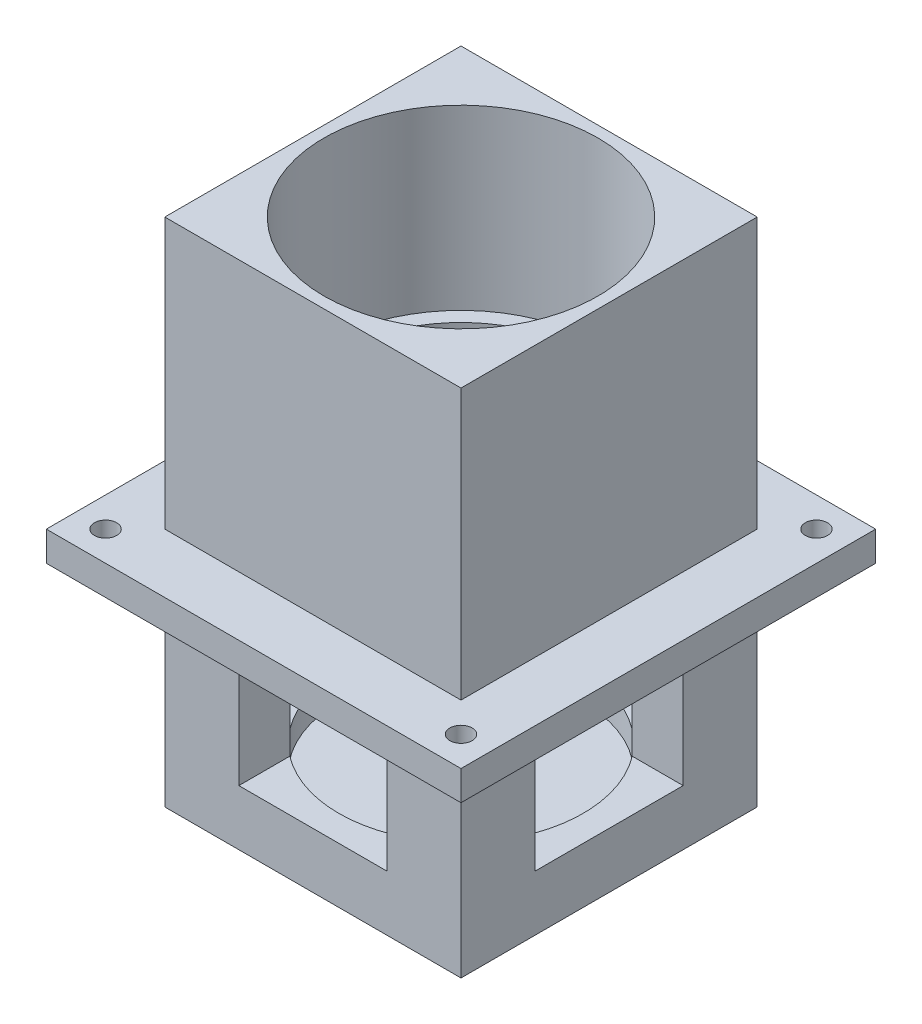
SolidWorks part; units mm, degrees
ref_plane "Front Plane" through (0, 0, 0) normal (0, 0, 1) x (1, 0, 0)
ref_plane "Top Plane" through (0, 0, 0) normal (0, 1, 0) x (1, 0, 0)
ref_plane "Right Plane" through (0, 0, 0) normal (1, 0, 0) x (0, 0, -1)
sketch "Sketch1" plane through (0, 0, 0) normal (0, 1, 0) x (1, 0, 0)
  line L1 (-20, -20) -> (20, -20)
  line L2 (-20, -20) -> (-20, 20)
  line L3 (-20, 20) -> (20, 20)
  line L4 (20, -20) -> (20, 20)
  line L5 (-20, -20) -> (20, 20) construction
  line L6 (-20, 20) -> (20, -20) construction
  point P0 (0, 0)
extrude "Boss-Extrude1" add sketch "Sketch1" along normal blind 90
sketch "Sketch2" plane through (0, 90, 0) normal (0, 1, 0) x (1, 0, 0)
  circle A0 centre (0, 0) radius 18.5
extrude "Cut-Extrude1" cut sketch "Sketch2" against normal blind 45
sketch "Sketch3" plane through (0, 45, 0) normal (0, 1, 0) x (1, 0, 0)
  circle A0 centre (0, 0) radius 16.5
extrude "Cut-Extrude2" cut sketch "Sketch3" against normal blind 41
sketch "Sketch4" plane through (0, 90, 0) normal (0, 1, 0) x (1, 0, 0)
  line L1 (-20, -20) -> (20, -20)
  line L2 (-20, -20) -> (-20, 20)
  line L3 (-20, 20) -> (20, 20)
  line L4 (20, -20) -> (20, 20)
  line L5 (-20, -20) -> (20, 20) construction
  line L6 (-20, 20) -> (20, -20) construction
  point P0 (0, 0)
extrude "Cut-Extrude3" cut sketch "Sketch4" against normal blind 21
sketch "Sketch6" plane through (0, 0, 20) normal (0, 0, 1) x (1, 0, 0)
  line L0 (0, 0) -> (0, 15) construction
  line L2 (-10, 7.5) -> (10, 7.5)
  line L3 (-10, 7.5) -> (-10, 22.5)
  line L4 (-10, 22.5) -> (10, 22.5)
  line L5 (10, 7.5) -> (10, 22.5)
  line L6 (-10, 7.5) -> (10, 22.5) construction
  line L7 (-10, 22.5) -> (10, 7.5) construction
extrude "Cut-Extrude4" cut sketch "Sketch6" against normal through all contours L3 L2 L5 L4
sketch "Sketch8" plane through (-20, 0, 0) normal (-1, 0, 0) x (0, 0, 1)
  line L0 (0, 0) -> (0, 15) construction
  line L2 (-10, 7.5) -> (10, 7.5)
  line L3 (-10, 7.5) -> (-10, 22.5)
  line L4 (-10, 22.5) -> (10, 22.5)
  line L5 (10, 7.5) -> (10, 22.5)
  line L6 (-10, 7.5) -> (10, 22.5) construction
  line L7 (-10, 22.5) -> (10, 7.5) construction
extrude "Cut-Extrude5" cut sketch "Sketch8" against normal through all contours L3 L2 L5 L4
sketch "Sketch11" plane through (0, 0, 20) normal (0, 0, 1) x (1, 0, 0)
  line L0 (0, 0) -> (0, 28.5) construction
  line L1 (-20, 0) -> (20, 0) construction
  line L2 (-20, 28.5) -> (20, 28.5) construction
  line L3 (20, 69) -> (20, 0) construction
  line L4 (-20, 28.5) -> (-20, 15.8) construction
  line L5 (-20, 69) -> (-20, 0) construction
  line L7 (-20, 15.8) -> (20, 15.8) construction
  line L8 (-20, 15.8) -> (-20, 69)
  line L9 (-20, 69) -> (20, 69)
  line L10 (20, 15.8) -> (20, 69)
  line L11 (-20, 28.5) -> (20, 28.5)
  line L12 (-20, 28.5) -> (-20, 0)
  line L13 (-20, 0) -> (20, 0)
  line L14 (20, 28.5) -> (20, 0)
  point P9 (0, 28.5)
sketch "Sketch16" plane through (0, 0, 20) normal (0, 0, 1) x (1, 0, 0)
  line L0 (20, 15.8) -> (20, 69) construction
  line L1 (-20, 28.5) -> (20, 28.5)
  line L2 (-20, 28.5) -> (-20, 32.5)
  line L3 (-20, 32.5) -> (20, 32.5)
  line L4 (20, 28.5) -> (20, 32.5)
extrude "Boss-Extrude3" add sketch "Sketch16" along normal blind 8
sketch "Sketch17" plane through (0, 0, -20) normal (0, 0, -1) x (-1, 0, 0)
  line L0 (20, 15.8) -> (20, 69) construction
  line L1 (-20, 28.5) -> (20, 28.5)
  line L2 (-20, 28.5) -> (-20, 32.5)
  line L3 (-20, 32.5) -> (20, 32.5)
  line L4 (20, 28.5) -> (20, 32.5)
extrude "Boss-Extrude4" add sketch "Sketch17" along normal blind 8
sketch "Sketch18" plane through (20, 0, 0) normal (1, 0, 0) x (0, 0, -1)
  line L1 (-28, 28.5) -> (28, 28.5)
  line L2 (-28, 28.5) -> (-28, 32.5)
  line L3 (-28, 32.5) -> (28, 32.5)
  line L4 (28, 28.5) -> (28, 32.5)
extrude "Boss-Extrude5" add sketch "Sketch18" along normal blind 8
sketch "Sketch19" plane through (-20, 0, 0) normal (-1, 0, 0) x (0, 0, 1)
  line L1 (-28, 28.5) -> (28, 28.5)
  line L2 (-28, 28.5) -> (-28, 32.5)
  line L3 (-28, 32.5) -> (28, 32.5)
  line L4 (28, 28.5) -> (28, 32.5)
extrude "Boss-Extrude6" add sketch "Sketch19" along normal blind 8 contours L2 L1 L4 L3
sketch "Sketch20" plane through (0, 32.5, 0) normal (0, 1, 0) x (1, 0, 0)
  line L0 (-28, 28) -> (-20, 20)
  line L1 (-20, 20) -> (-28, 20)
  line L2 (-28, 28) -> (-28, -28) construction
  line L3 (-28, 20) -> (-20, 28)
  line L4 (-28, 28) -> (28, 28) construction
  circle A0 centre (-24, 24) radius 1.5
  circle A1 centre (24, 24) radius 1.5
  circle A2 centre (24, -24) radius 1.5
  circle A3 centre (-24, -24) radius 1.5
  point P12 (0, 0)
  point P14 (0, 0)
  dimension "D1" = 2
  dimension "D2" = 2
extrude "Cut-Extrude9" cut sketch "Sketch20" against normal through all contours A0 | A3 | A2 | A1
